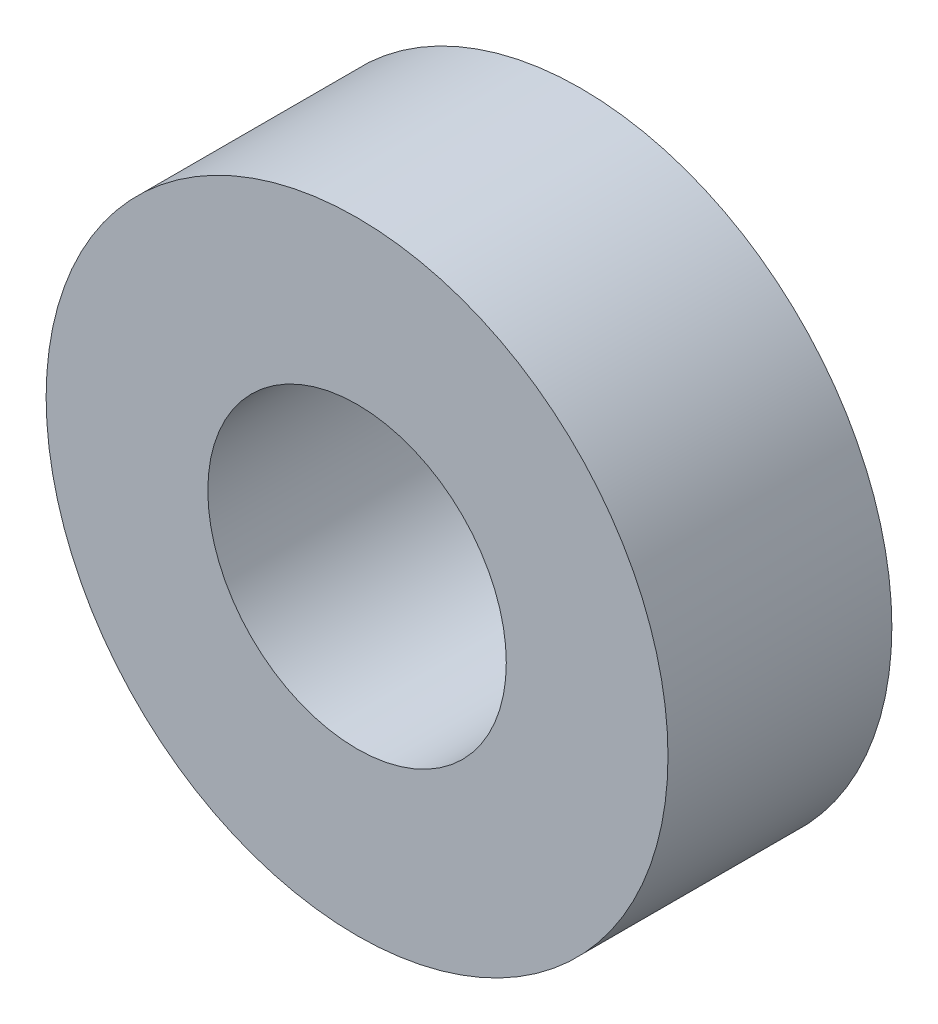
SolidWorks part; units mm, degrees
material "VITON"
ref_plane "Front Plane" through (0, 0, 0) normal (0, 0, 1) x (1, 0, 0)
ref_plane "Top Plane" through (0, 0, 0) normal (0, 1, 0) x (1, 0, 0)
ref_plane "Right Plane" through (0, 0, 0) normal (1, 0, 0) x (0, 0, -1)
sketch "BaseS" plane through (0, 0, 0) normal (0, 0, 1) x (1, 0, 0)
  circle A0 centre (0, 0) radius 6.25
  circle A1 centre (0, 0) radius 3
  dimension "OD" = 12.5
  dimension "RefDia" = 6
  dimension "IDControl" = 3.25
extrude "BASE" add sketch "BaseS" along normal blind 4.5
